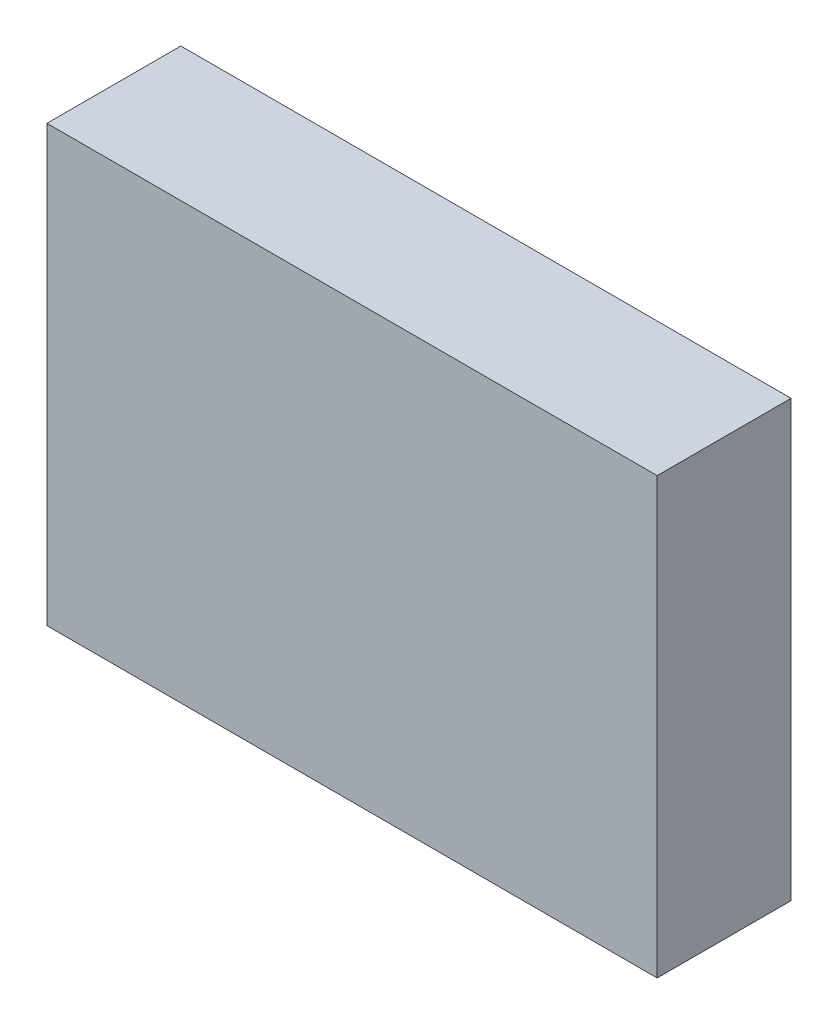
SolidWorks part; units mm, degrees
ref_plane "前视基准面" through (0, 0, 0) normal (0, 0, 1) x (1, 0, 0)
ref_plane "上视基准面" through (0, 0, 0) normal (0, 1, 0) x (1, 0, 0)
ref_plane "右视基准面" through (0, 0, 0) normal (1, 0, 0) x (0, 0, -1)
sketch "Sketch1" plane through (0, 0, 0) normal (0, 0, 1) x (1, 0, 0)
  line L1 (80.3934, -22.5008) -> (103.1808, -22.5008)
  line L2 (80.3934, -22.5008) -> (80.3934, -38.7473)
  line L3 (80.3934, -38.7473) -> (103.1808, -38.7473)
  line L4 (103.1808, -22.5008) -> (103.1808, -38.7473)
extrude "Boss-Extrude1" add sketch "Sketch1" along normal blind 5
